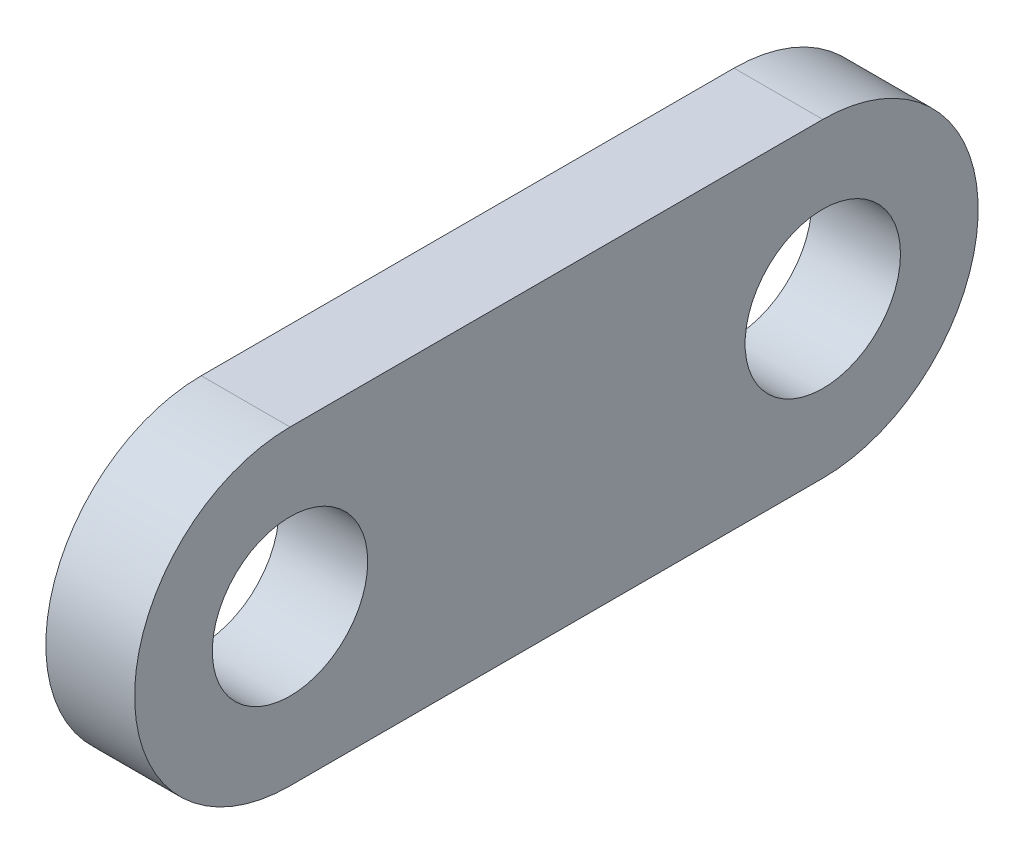
SolidWorks part; units mm, degrees
ref_plane "Front Plane" through (0, 0, 0) normal (0, 0, 1) x (1, 0, 0)
ref_plane "Top Plane" through (0, 0, 0) normal (0, 1, 0) x (1, 0, 0)
ref_plane "Right Plane" through (0, 0, 0) normal (1, 0, 0) x (0, 0, -1)
sketch "Sketch1" plane through (0, 0, 0) normal (1, 0, 0) x (0, 0, -1)
  line L0 (-6, 4.2733) -> (6, 4.2733)
  line L1 (-6, -2.7267) -> (6, -2.7267)
  arc A0 (-6, -2.7267) -> (-6, 4.2733) centre (-6, 0.7733) cw
  arc A1 (6, 4.2733) -> (6, -2.7267) centre (6, 0.7733) cw
  circle A2 centre (-6, 0.7733) radius 1.75
  circle A3 centre (6, 0.7733) radius 1.75
  point P4 (0, 4.2733)
  dimension "D2" = 3.5
  dimension "D1" = 12
  dimension "D3" = 7
extrude "Boss-Extrude1" add sketch "Sketch1" along normal blind 2
